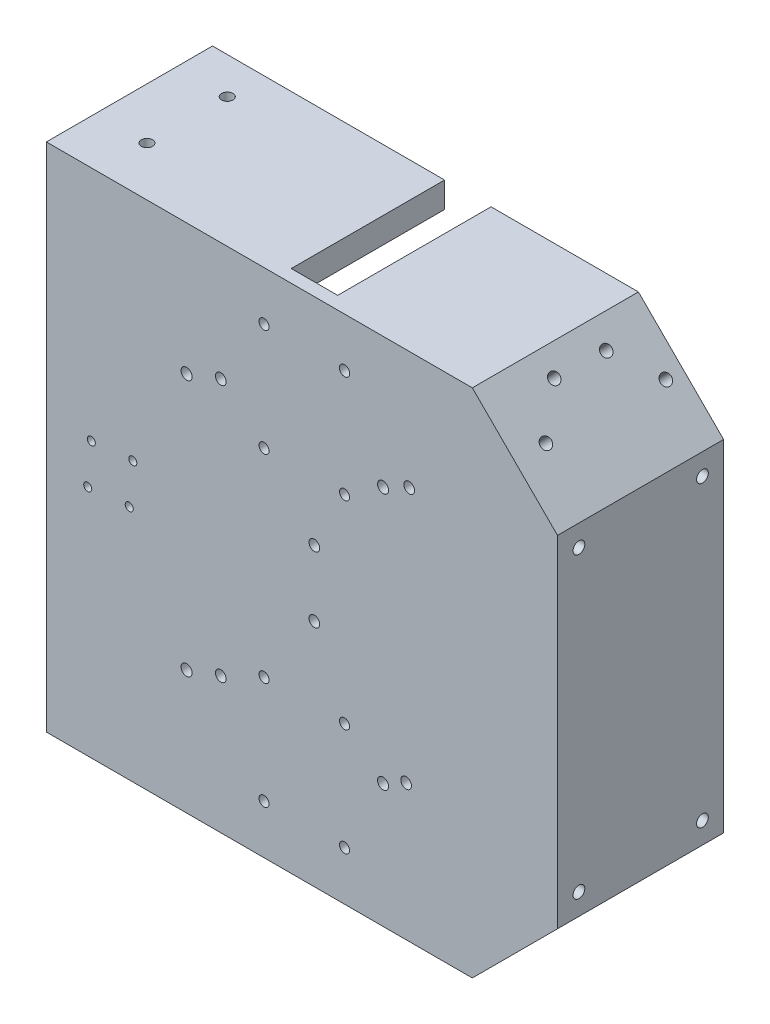
SolidWorks part; units mm, degrees
ref_plane "Front Plane" through (0, 0, 0) normal (0, 0, 1) x (1, 0, 0)
ref_plane "Top Plane" through (0, 0, 0) normal (0, 1, 0) x (1, 0, 0)
ref_plane "Right Plane" through (0, 0, 0) normal (1, 0, 0) x (0, 0, -1)
sketch "Sketch1" plane through (0, 0, 0) normal (0, 0, 1) x (1, 0, 0)
  line L0 (-19.05, 0) -> (133.35, 0) construction
  line L1 (57.15, 69.85) -> (57.15, -69.85) construction
  line L2 (-19.05, 19.05) -> (-19.05, -19.05) construction
  line L3 (133.35, -50.8) -> (107.95, -76.2)
  line L4 (107.95, 76.2) -> (-19.05, 76.2)
  line L5 (133.35, 50.8) -> (133.35, -50.8)
  line L6 (107.95, -76.2) -> (-19.05, -76.2)
  line L7 (-19.05, 76.2) -> (-19.05, -76.2)
  line L8 (133.35, 76.2) -> (-19.05, -76.2) construction
  line L9 (133.35, -76.2) -> (-19.05, 76.2) construction
  line L10 (107.95, 76.2) -> (133.35, 50.8)
  point P6 (57.15, 0)
  point P10 (57.15, 0)
  dimension "D1" = 139.7
  dimension "D2" = 152.4
  dimension "D3" = 152.4
extrude "Boss-Extrude1" add sketch "Sketch1" along normal blind 3.81
sketch "Sketch2" plane through (0, 0, 0) normal (0, 0, -1) x (-1, 0, 0)
  line L0 (-107.95, -76.2) -> (-133.35, -50.8)
  line L1 (-107.95, -76.2) -> (-133.35, -50.8)
  line L2 (-133.35, -50.8) -> (-133.35, 50.8)
  line L3 (-133.35, -50.8) -> (-133.35, 50.8)
  line L4 (-133.35, 50.8) -> (-107.95, 76.2)
  line L5 (-133.35, 50.8) -> (-107.95, 76.2)
  line L6 (-107.95, 76.2) -> (19.05, 76.2)
  line L7 (-107.95, 76.2) -> (-63.9967, 76.2)
  line L8 (19.05, 76.2) -> (19.05, -76.2)
  line L9 (19.05, 76.2) -> (19.05, 24.364)
  line L10 (19.05, -76.2) -> (-107.95, -76.2)
  line L11 (19.05, -76.2) -> (-50.1528, -76.2)
  line L12 (-104.7937, 68.58) -> (-63.9967, 68.58)
  line L13 (11.43, 68.58) -> (11.43, 24.364)
  line L14 (11.43, -68.58) -> (-50.1528, -68.58)
  line L15 (-104.7937, -68.58) -> (-125.73, -47.6437)
  line L16 (-125.73, -47.6437) -> (-125.73, 47.6437)
  line L17 (-125.73, 47.6437) -> (-104.7937, 68.58)
  line L18 (-56.7335, 54.6698) -> (-56.7335, 42.0902) construction
  line L19 (11.43, -24.364) -> (19.05, -24.364)
  line L21 (11.43, 24.364) -> (19.05, 24.364)
  line L26 (-63.9967, 68.58) -> (-63.9967, 76.2)
  line L28 (-50.1528, 68.58) -> (-50.1528, 76.2)
  line L31 (19.05, -24.364) -> (19.05, -76.2)
  line L33 (-50.1528, -68.58) -> (-50.1528, -76.2)
  line L35 (-63.9967, -68.58) -> (-63.9967, -76.2)
  line L36 (-63.9967, -76.2) -> (-107.95, -76.2)
  line L37 (19.05, -76.2) -> (-107.95, -76.2) construction
  line L38 (-63.9967, -68.58) -> (-104.7937, -68.58)
  line L39 (11.43, -68.58) -> (-104.7937, -68.58) construction
  line L40 (-50.1528, 76.2) -> (19.05, 76.2)
  line L41 (-107.95, 76.2) -> (19.05, 76.2) construction
  line L42 (-50.1528, 68.58) -> (11.43, 68.58)
  line L43 (-104.7937, 68.58) -> (11.43, 68.58) construction
  line L44 (19.05, 76.2) -> (19.05, -76.2) construction
  line L46 (11.43, -24.364) -> (11.43, -68.58)
  line L47 (11.43, 68.58) -> (11.43, -68.58) construction
  point P12 (0, 0)
  point P18 (-56.7335, 48.38)
  dimension "D1" = 7.62
extrude "Boss-Extrude2" add sketch "Sketch2" along normal blind 45.72
sketch "Sketch7" plane through (0, 0, 0) normal (0, 0, -1) x (-1, 0, 0)
  circle A0 centre (-6.7175, 6.7175) radius 1.2
  circle A1 centre (5.6569, 5.6569) radius 1.2
  circle A3 centre (-5.6569, -5.6569) radius 1.2
  circle A4 centre (6.7175, -6.7175) radius 1.2
extrude "Cut-Extrude2" cut sketch "Sketch7" against normal blind 17.78
sketch "Sketch8" plane through (0, 0, -45.72) normal (0, 0, -1) x (-1, 0, 0)
  line L2 (-107.95, 76.2) -> (-133.35, 50.8)
  line L6 (-133.35, 50.8) -> (-86.1724, 50.8)
  line L8 (-86.1724, 50.8) -> (-85.9733, 76.2)
  line L12 (-63.9967, 76.2) -> (-107.95, 76.2) construction
  line L30 (-85.9733, 76.2) -> (-107.95, 76.2)
  line L39 (-133.35, 0) -> (-60.2492, 0)
  line L43 (-20.6267, -76.2) -> (-20.6267, -50.8)
  line L44 (19.05, 76.2) -> (-20.6267, 76.2)
  line L45 (-133.35, 50.8) -> (-133.35, -50.8) construction
  line L46 (19.05, 76.2) -> (19.05, 50.8)
  line L47 (19.05, 50.8) -> (-20.6267, 50.8)
  line L48 (-20.6267, 76.2) -> (-20.6267, 50.8)
  line L49 (19.05, -50.8) -> (-20.6267, -50.8)
  line L50 (19.05, -76.2) -> (19.05, -50.8)
  line L51 (19.05, -76.2) -> (-20.6267, -76.2)
  line L52 (-85.9733, -76.2) -> (-107.95, -76.2)
  line L53 (-86.1724, -50.8) -> (-85.9733, -76.2)
  line L54 (-133.35, -50.8) -> (-86.1724, -50.8)
  line L55 (-107.95, -76.2) -> (-133.35, -50.8)
  line M26 (19.05, 76.2) -> (-50.1528, 76.2)
  line M28 (-50.1528, 68.58) -> (11.43, 68.58)
  line M29 (11.43, 68.58) -> (11.43, 24.364)
  line M31 (19.05, 24.364) -> (19.05, 76.2)
extrude "Boss-Extrude3" add sketch "Sketch8" against normal blind 3.81 contours L48 L47 M28 M29 | L8 L30 L2 L6 | L55 L52 L53 L54 | L51 L50 L49 L43 | L48 L47 M26 M28 M29 M31
sketch "Sketch9" plane through (0, 0, -45.72) normal (0, 0, -1) x (-1, 0, 0)
  line L0 (-133.35, 0) -> (19.05, 0) construction
  line L1 (-133.35, 50.8) -> (-133.35, -50.8) construction
  line L2 (19.05, 24.364) -> (19.05, -24.364) construction
  circle A0 centre (-92.5422, 57.577) radius 1.65
  circle A1 centre (-108.8202, 57.577) radius 1.65
  circle A2 centre (-14.2391, 57.577) radius 1.65
  circle A3 centre (1.7583, 57.577) radius 1.65
  circle A4 centre (1.7583, -57.577) radius 1.65
  circle A5 centre (-14.2391, -57.577) radius 1.65
  circle A6 centre (-92.5422, -57.577) radius 1.65
  circle A7 centre (-108.8202, -57.577) radius 1.65
  dimension "D1" = 3.3
  dimension "D2" = 3.3
  dimension "D3" = 3.3
  dimension "D4" = 3.3
extrude "Cut-Extrude3" cut sketch "Sketch9" against normal blind 3.81
sketch "Sketch10" plane through (0, 0, 0) normal (0, 0, -1) x (-1, 0, 0)
  circle A0 centre (-69.8482, 61.58) radius 1.5478
  circle A1 centre (-45.8482, 61.58) radius 1.5
  circle A2 centre (-45.8482, 29.58) radius 1.5
  circle A4 centre (-69.8482, 29.58) radius 1.5
  circle A5 centre (-69.8482, -29.58) radius 1.5
  circle A6 centre (-45.8482, -29.58) radius 1.5
  circle A7 centre (-69.8482, -61.58) radius 1.5
  circle A8 centre (-45.8482, -61.58) radius 1.5
extrude "Cut-Extrude4" cut sketch "Sketch10" against normal blind 7.62
sketch "Sketch11" plane through (-19.05, 0, 0) normal (-1, 0, 0) x (0, 0, 1)
  line L0 (-45.72, -24.364) -> (3.81, -76.2) construction
  line L1 (3.81, 0) -> (-44.831, 0) construction
  line L2 (-20.955, -50.282) -> (-45.72, -50.282) construction
  line L3 (-20.955, -50.282) -> (-20.955, -76.2) construction
  line L8 (3.81, 76.2) -> (-45.72, 76.2)
  line L9 (-45.72, 76.2) -> (-45.72, 24.364)
  line L10 (-45.72, 24.364) -> (0, 24.364)
  line L11 (0, 24.364) -> (0, -24.364)
  line L12 (0, -24.364) -> (-45.72, -24.364)
  line L13 (-45.72, -24.364) -> (-45.72, -76.2)
  line L14 (-45.72, -76.2) -> (3.81, -76.2)
  line L15 (3.81, -76.2) -> (3.81, 76.2)
  line L16 (3.81, 76.2) -> (-45.72, 76.2) construction
  line L17 (-45.72, 76.2) -> (-45.72, 24.364) construction
  line L18 (-45.72, 24.364) -> (0, 24.364) construction
  line L19 (0, 24.364) -> (0, -24.364) construction
  line L20 (0, -24.364) -> (-45.72, -24.364) construction
  line L21 (-45.72, -24.364) -> (-45.72, -76.2) construction
  line L22 (-45.72, -76.2) -> (3.81, -76.2) construction
  line L23 (3.81, -76.2) -> (3.81, 76.2) construction
  circle A0 centre (-32.0993, -62.639) radius 1.7
  circle A1 centre (-9.8107, -62.639) radius 1.7
  circle A2 centre (-9.8107, -37.925) radius 1.7
  circle A3 centre (-32.0993, -37.925) radius 1.7
  circle A4 centre (-9.8107, 37.925) radius 1.7
  circle A5 centre (-9.8107, 62.639) radius 1.7
  circle A6 centre (-32.0993, 37.925) radius 1.7
  circle A7 centre (-32.0993, 62.639) radius 1.7
  dimension "D4" = 3.4
  dimension "D2" = 12.357
  dimension "D3" = 11.1443
  dimension "D1" = 0
extrude "Cut-Extrude5" cut sketch "Sketch11" against normal up to next
sketch "Sketch12" plane through (0, 76.2, 0) normal (0, 1, 0) x (1, 0, 0)
  circle A0 centre (-3.7599, 34.8267) radius 1.7
  circle A1 centre (-3.7599, 10.8933) radius 1.6916
extrude "Cut-Extrude6" cut sketch "Sketch12" against normal through all
sketch "Sketch13" plane through (92.075, 92.075, 0) normal (0.7071, 0.7071, 0) x (0, 0, -1)
  circle A0 centre (30.9392, -29.8012) radius 1.65
  circle A1 centre (40.5314, -41.3413) radius 1.65
  circle A2 centre (5.4954, -40.3273) radius 1.65
  circle A3 centre (15.739, -29.3613) radius 1.65
extrude "Cut-Extrude7" cut sketch "Sketch13" against normal up to next
sketch "Sketch14" plane through (92.075, -92.075, 0) normal (0.7071, -0.7071, 0) x (0, 0, -1)
  circle A0 centre (40.2246, 40.3273) radius 1.6846
  circle A1 centre (29.981, 29.3613) radius 1.65
  circle A2 centre (14.7808, 29.8012) radius 1.5613
  circle A3 centre (5.1886, 41.3413) radius 1.65
extrude "Cut-Extrude8" cut sketch "Sketch14" against normal up to next
sketch "Sketch15" plane through (0, 0, 3.81) normal (0, 0, 1) x (1, 0, 0)
  circle A0 centre (81.3428, -39.2638) radius 1.65
  circle A1 centre (22.7484, -39.2638) radius 1.65
  circle A2 centre (81.3428, 37.2371) radius 1.65
  circle A3 centre (22.7484, 37.2371) radius 1.65
extrude "Cut-Extrude9" cut sketch "Sketch15" against normal up to next
sketch "Sketch16" plane through (133.35, 0, 0) normal (1, 0, 0) x (0, 0, -1)
  circle A0 centre (39.4077, 44.45) radius 1.7501
  circle A1 centre (2.5777, 44.45) radius 1.7501
  circle A2 centre (39.4077, -44.45) radius 1.7501
  circle A3 centre (2.5777, -44.45) radius 1.7501
extrude "Cut-Extrude10" cut sketch "Sketch16" against normal up to next
sketch "Sketch17" plane through (0, 0, 0) normal (0, 0, -1) x (-1, 0, 0)
  circle A0 centre (-89.1357, 41.0197) radius 1.6
  circle A1 centre (-32.9541, 41.0197) radius 1.6
  circle A2 centre (-60.8497, 11.9847) radius 1.6
  circle A3 centre (-60.8497, -7.6452) radius 1.6
  circle A4 centre (-32.9541, -35.676) radius 1.6
  circle A5 centre (-88.2117, -35.676) radius 1.6
extrude "Cut-Extrude11" cut sketch "Sketch17" against normal up to next
